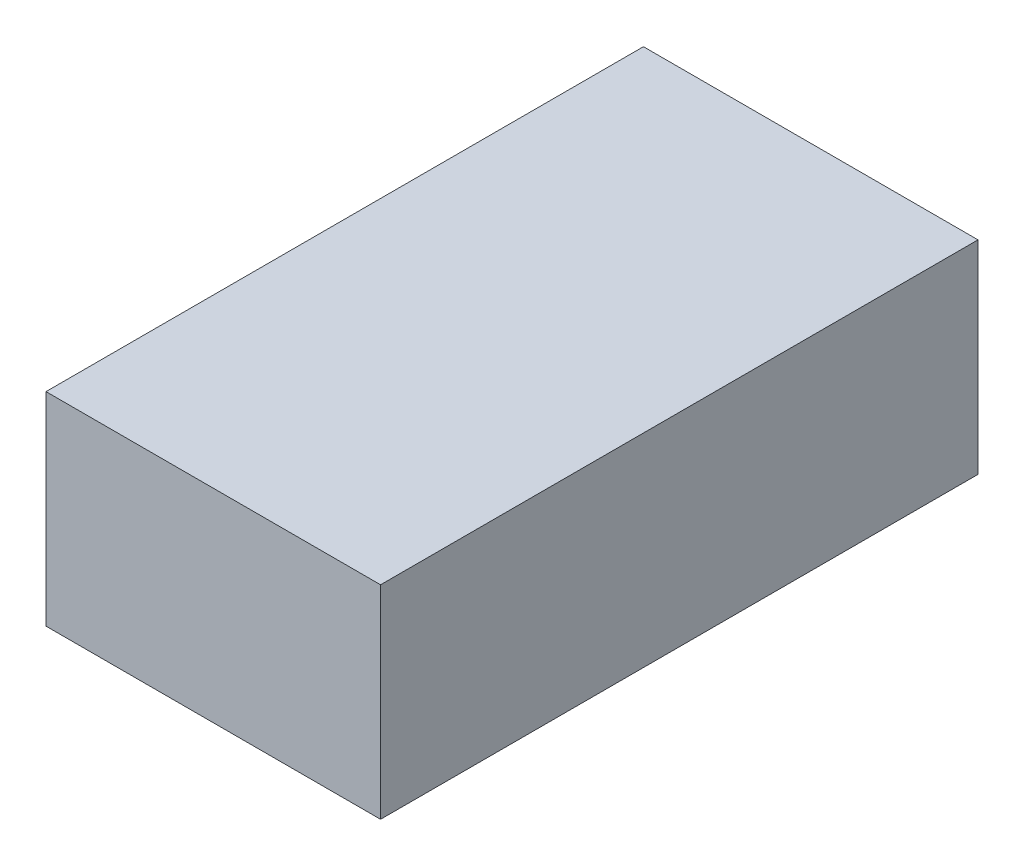
SolidWorks part; units mm, degrees
ref_plane "Plano frontal" through (0, 0, 0) normal (0, 0, 1) x (1, 0, 0)
ref_plane "Plano superior" through (0, 0, 0) normal (0, 1, 0) x (1, 0, 0)
ref_plane "Plano direito" through (0, 0, 0) normal (1, 0, 0) x (0, 0, -1)
sketch "Esboço1" plane through (0, 0, 0) normal (0, 1, 0) x (1, 0, 0)
  line L1 (0, 0) -> (28, 0)
  line L2 (0, 0) -> (0, 50)
  line L3 (0, 50) -> (28, 50)
  line L4 (28, 0) -> (28, 50)
  dimension "D1" = 50
  dimension "D2" = 28
extrude "Ressalto-extrusão1" add sketch "Esboço1" along normal blind 17
